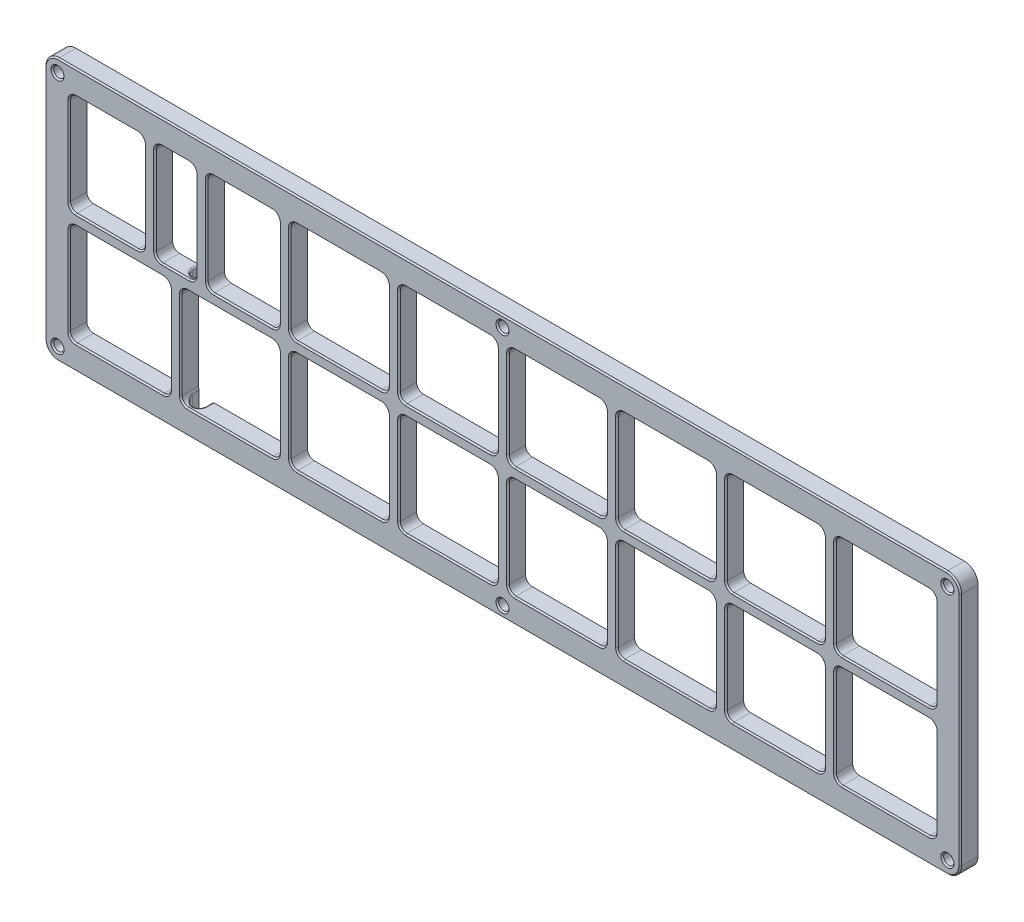
SolidWorks part; units mm, degrees
ref_plane "Front Plane" through (0, 0, 0) normal (0, 0, 1) x (1, 0, 0)
ref_plane "Top Plane" through (0, 0, 0) normal (0, 1, 0) x (1, 0, 0)
ref_plane "Right Plane" through (0, 0, 0) normal (1, 0, 0) x (0, 0, -1)
sketch "Sketch1" plane through (0, 0, 0) normal (0, 0, 1) x (1, 0, 0)
  line L1 (0, 40.25) -> (0, -40.25) construction
  line L2 (0, 0) -> (-160.25, 0) construction
  line L3 (-80.125, 0) -> (-80.125, 40.25) construction
  line L4 (168.25, -43.25) -> (168.25, 43.25)
  line L5 (163.25, 48.25) -> (-163.25, 48.25)
  line L6 (-168.25, 43.25) -> (-168.25, -43.25)
  line L7 (-163.25, -48.25) -> (163.25, -48.25)
  line L8 (168.25, -43.25) -> (168.25, 43.25)
  line L9 (163.25, 48.25) -> (-163.25, 48.25)
  line L10 (-168.25, 43.25) -> (-168.25, -43.25)
  line L11 (-163.25, -48.25) -> (163.25, -48.25)
  line L12 (-80.125, 20.125) -> (-160.25, 20.125) construction
  line L13 (-160.25, -40.25) -> (160.25, -40.25)
  line L14 (-160.25, 40.25) -> (-160.25, -40.25)
  line L15 (160.25, 40.25) -> (-160.25, 40.25)
  line L16 (160.25, -40.25) -> (160.25, 40.25)
  line L17 (-160.25, -40.25) -> (160.25, -40.25)
  line L18 (-160.25, 40.25) -> (-160.25, -40.25)
  line L19 (160.25, 40.25) -> (-160.25, 40.25)
  line L20 (160.25, -40.25) -> (160.25, 40.25)
  line L21 (-120.1875, 20.125) -> (-120.1875, 40.25) construction
  line L22 (-120.1875, 40.25) -> (-120.1875, -40.25) construction
  line L23 (-80.125, 40.25) -> (-80.125, -40.25) construction
  line L24 (-80.125, 20.125) -> (0, 20.125) construction
  line L25 (-40.0625, 20.125) -> (-40.0625, 40.25) construction
  line L26 (-40.0625, 40.25) -> (-40.0625, -40.25) construction
  line L27 (-42.0625, 40.25) -> (-42.0625, -40.25)
  line L28 (-82.125, 40.25) -> (-82.125, -40.25)
  line L29 (-122.1875, 40.25) -> (-122.1875, -40.25)
  line L30 (0, 2) -> (-160.25, 2)
  line L31 (-2, 40.25) -> (-2, -40.25)
  line L32 (-38.0625, 40.25) -> (-38.0625, -40.25)
  line L33 (-78.125, 40.25) -> (-78.125, -40.25)
  line L34 (-118.1875, 40.25) -> (-118.1875, -40.25)
  line L35 (0, -2) -> (-160.25, -2)
  line L36 (2, 40.25) -> (2, -40.25)
  line L37 (0, -2) -> (160.25, -2)
  line L38 (0, 2) -> (160.25, 2)
  line L39 (38.0625, 40.25) -> (38.0625, -40.25)
  line L40 (42.0625, 40.25) -> (42.0625, -40.25)
  line L41 (78.125, 40.25) -> (78.125, -40.25)
  line L42 (82.125, 40.25) -> (82.125, -40.25)
  line L43 (118.1875, 40.25) -> (118.1875, -40.25)
  line L44 (122.1875, 40.25) -> (122.1875, -40.25)
  line L45 (-159.25, 39.25) -> (-160.25, 39.25) construction
  line L46 (159.25, -39.25) -> (-159.25, -39.25)
  line L47 (159.25, -39.25) -> (159.25, 39.25)
  line L48 (159.25, 39.25) -> (-159.25, 39.25)
  line L49 (-159.25, -39.25) -> (-159.25, 39.25)
  line L50 (159.25, -39.25) -> (-159.25, 39.25) construction
  line L51 (159.25, 39.25) -> (-159.25, -39.25) construction
  line L52 (-159.25, 39.25) -> (-159.25, 40.25) construction
  circle A0 centre (163.5178, 43.5178) radius 1.75 construction
  circle A1 centre (0, 44.25) radius 1.75 construction
  circle A2 centre (-163.5178, 43.5178) radius 1.75 construction
  circle A3 centre (-163.5178, -43.5178) radius 1.75 construction
  arc A4 (163.25, -48.25) -> (168.25, -43.25) centre (163.25, -43.25) ccw
  arc A5 (168.25, 43.25) -> (163.25, 48.25) centre (163.25, 43.25) ccw
  arc A6 (-163.25, 48.25) -> (-168.25, 43.25) centre (-163.25, 43.25) ccw
  arc A7 (-168.25, -43.25) -> (-163.25, -48.25) centre (-163.25, -43.25) ccw
  arc A8 (163.25, -48.25) -> (168.25, -43.25) centre (163.25, -43.25) ccw
  arc A9 (168.25, 43.25) -> (163.25, 48.25) centre (163.25, 43.25) ccw
  arc A10 (-163.25, 48.25) -> (-168.25, 43.25) centre (-163.25, 43.25) ccw
  arc A11 (-168.25, -43.25) -> (-163.25, -48.25) centre (-163.25, -43.25) ccw
  circle A12 centre (0, -44.25) radius 1.75 construction
  circle A13 centre (163.5178, -43.5178) radius 1.75 construction
  circle A14 centre (163.5178, 43.5178) radius 1.75 construction
  circle A15 centre (0, 44.25) radius 1.75 construction
  circle A16 centre (-163.5178, 43.5178) radius 1.75 construction
  circle A17 centre (-163.5178, -43.5178) radius 1.75 construction
  circle A18 centre (0, -44.25) radius 1.75 construction
  circle A19 centre (163.5178, -43.5178) radius 1.75 construction
  circle A20 centre (-163.5178, 43.5178) radius 1.9
  circle A21 centre (0, 44.25) radius 1.9
  circle A22 centre (163.5178, 43.5178) radius 1.9
  circle A23 centre (163.5178, -43.5178) radius 1.9
  circle A24 centre (0, -44.25) radius 1.9
  circle A25 centre (-163.5178, -43.5178) radius 1.9
  dimension "D5" = 3.8
  dimension "D6" = 1
  dimension "D1" = 0
  dimension "D2" = 0
  dimension "D3" = 2
  dimension "D4" = 2
extrude "Boss-Extrude1" add sketch "Sketch1" along normal blind 6.5 contours L10 A11 L11 A8 L8 A9 L9 A10 A19 A18 A17 A16 A15 A14 L20 L17 L18 L19 | L35 L29 L30 L18 | L34 L19 L29 L30 | L35 L34 L30 L29 | L34 L35 L29 L17 | L35 L28 L30 L34 | L35 L33 L30 L28 | L33 L19 L28 L30 | L33 L35 L28 L17 | L35 L27 L30 L33 | L32 L19 L27 L30 | L32 L35 L27 L17 | L35 L32 L30 L27 | L35 L31 L30 L32 | L37 L35 L31 L17 L36 | L38 L30 L31 L35 L37 L36 | L30 L38 L36 L19 L31 | L39 L38 L36 L37 | L40 L19 L39 L38 | L40 L38 L39 L37 | L40 L37 L39 L17 | L41 L38 L40 L37 | L42 L19 L41 L38 | L42 L38 L41 L37 | L42 L37 L41 L17 | L43 L38 L42 L37 | L44 L19 L43 L38 | L44 L38 L43 L37 | L44 L37 L43 L17 | L38 L44 L37 L20 | L30 L49 L48 L29 L19 L18 | L48 L34 L19 L29 | L48 L28 L19 L34 | L48 L33 L19 L28 | L48 L27 L19 L33 | L48 L32 L19 L27 | L48 L31 L19 L32 | L48 L36 L19 L31 | L48 L39 L19 L36 | L48 L40 L19 L39 | L48 L41 L19 L40 | L48 L42 L19 L41 | L48 L43 L19 L42 | L48 L44 L19 L43 | L48 L47 L38 L20 L19 L44 | L47 L37 L20 L38 | L47 L46 L44 L17 L20 L37 | L44 L46 L43 L17 | L43 L46 L42 L17 | L42 L46 L41 L17 | L41 L46 L40 L17 | L40 L46 L39 L17 | L39 L46 L36 L17 | L36 L46 L31 L17 | L31 L46 L32 L17 | L32 L46 L27 L17 | L27 L46 L33 L17 | L33 L46 L28 L17 | L28 L46 L34 L17 | L34 L46 L29 L17 | L46 L49 L35 L18 L17 L29 | L35 L49 L30 L18
sketch "Sketch2" plane through (0, 0, 6.5) normal (0, 0, 1) x (1, 0, 0)
  line L0 (-122.1875, 39.25) -> (-122.1875, 2) construction
  line L1 (-122.1875, 39.25) -> (-118.1875, 39.25)
  line L2 (-122.1875, 39.25) -> (-122.1875, 2)
  line L3 (-122.1875, 2) -> (-118.1875, 2)
  line L4 (-118.1875, 39.25) -> (-118.1875, 2)
  line L5 (-122.1875, 39.25) -> (-159.25, 39.25) construction
  point P6 (-122.1875, 39.25)
  point P9 (-122.1875, 39.25)
extrude "Cut-Extrude1" cut sketch "Sketch2" against normal up to next
sketch "Sketch3" plane through (0, 0, 0) normal (0, 0, -1) x (-1, 0, 0)
  line L0 (120.1875, 39.25) -> (120.1875, 2) construction
  line L2 (82.125, 2) -> (159.25, 2) construction
  line L3 (78.125, 2) -> (82.125, 2) construction
  line L4 (118.1875, -2) -> (122.1875, -2) construction
  line L5 (108.6875, 39.25) -> (112.6875, 39.25)
  line L6 (108.6875, 39.25) -> (108.6875, 2)
  line L7 (108.6875, 2) -> (112.6875, 2)
  line L8 (112.6875, 39.25) -> (112.6875, 2)
  line L9 (131.6875, 39.25) -> (127.6875, 39.25)
  line L10 (131.6875, 39.25) -> (131.6875, 2)
  line L11 (131.6875, 2) -> (127.6875, 2)
  line L12 (127.6875, 39.25) -> (127.6875, 2)
  line L13 (82.125, 39.25) -> (159.25, 39.25) construction
  point P2 (108.6875, 39.25)
  point P6 (120.1875, -2)
  point P24 (120.1875, 39.25)
  dimension "D1" = 15
extrude "Boss-Extrude2" add sketch "Sketch3" against normal up to surface (6.5 mm away) up to face at (-120.6875, 20.625, 6.5)
sketch "Sketch4" plane through (0, -48.25, 0) normal (0, -1, 0) x (1, 0, 0)
  line L0 (-82.125, 6.5) -> (-118.1875, 6.5) construction
  line L1 (-82.125, 6.5) -> (-118.1875, 6.5) construction
  line L2 (-112.6875, 6.5) -> (-127.6875, 6.5) construction
  line L3 (-112.6875, 6.5) -> (-127.6875, 6.5) construction
  line L4 (-118.1875, 6.5) -> (-112.6875, 6.5) construction
  line L5 (-115.4375, 6.5) -> (-115.4375, 0) construction
  line L6 (-163.25, 0) -> (163.25, 0) construction
  line L7 (-117.9375, 2.5) -> (-117.9375, 0)
  line L8 (-112.9375, 2.5) -> (-112.9375, 0)
  line L9 (-117.9375, 0) -> (-112.9375, 0)
  arc A0 (-112.9375, 2.5) -> (-117.9375, 2.5) centre (-115.4375, 2.5) ccw
  point P4 (-115.4375, 6.5)
  dimension "D1" = 5
extrude "Cut-Extrude2" cut sketch "Sketch4" against normal up to surface (50.25 mm away) up to face at (-95.4062, 2, 3.25)
fillet "Fillet1" radius 2.5 68 edges at (-159.25, -2, 3.25) (-159.25, -39.25, 3.25) (-122.1875, -39.25, 3.25) (-38.0625, 39.25, 3.25) (-38.0625, 2, 3.25) (-2, 2, 3.25) (-118.1875, -2, 3.25) (-118.1875, -39.25, 3.25) (-82.125, -39.25, 3.25) (-78.125, 39.25, 3.25) (-78.125, 2, 3.25) (-42.0625, 2, 3.25) (-78.125, -2, 3.25) (-78.125, -39.25, 3.25) (-42.0625, -39.25, 3.25) (38.0625, 2, 3.25) (2, 39.25, 3.25) (2, 2, 3.25) (78.125, 2, 3.25) (42.0625, 2, 3.25) (118.1875, 2, 3.25) (82.125, 2, 3.25) (159.25, 2, 3.25) (122.1875, 2, 3.25) (122.1875, -39.25, 3.25) (159.25, -39.25, 3.25) (122.1875, -2, 3.25) (82.125, -39.25, 3.25) (118.1875, -39.25, 3.25) (82.125, -2, 3.25) (42.0625, -39.25, 3.25) (78.125, -39.25, 3.25) (42.0625, -2, 3.25) (2, -39.25, 3.25) (38.0625, -39.25, 3.25) (2, -2, 3.25) (-38.0625, -2, 3.25) (-38.0625, -39.25, 3.25) (-2, -39.25, 3.25) (-159.25, 39.25, 3.25) (-159.25, 2, 3.25) (-131.6875, 2, 3.25) (-127.6875, 2, 3.25) (-112.6875, 2, 3.25) (-127.6875, 39.25, 3.25) (-108.6875, 2, 3.25) (-82.125, 2, 3.25) (-108.6875, 39.25, 3.25) (42.0625, 39.25, 3.25) (82.125, 39.25, 3.25) (122.1875, 39.25, 3.25) (-122.1875, -2, 3.25) (-82.125, -2, 3.25) (-42.0625, -2, 3.25) (-2, -2, 3.25) (38.0625, -2, 3.25) (78.125, -2, 3.25) (118.1875, -2, 3.25) (159.25, -2, 3.25) (-131.6875, 39.25, 3.25) (-112.6875, 39.25, 3.25) (-82.125, 39.25, 3.25) (-42.0625, 39.25, 3.25) (-2, 39.25, 3.25) (38.0625, 39.25, 3.25) (78.125, 39.25, 3.25) (118.1875, 39.25, 3.25) (159.25, 39.25, 3.25)
fillet "Fillet2" radius 0.5 15 edges at (-117.9375, 2, 1.25) (-112.9375, 3.4103, 1.25) (-113.3623, 2.7916, 3.8941) (-112.9375, -2, 1.25) (-117.9375, -3.4103, 1.25) (-117.5127, -2.7916, 3.8941) (-112.9375, -39.25, 1.25) (-117.9375, -37.8397, 1.25) (-117.1466, -38.78, 4.3245) (-117.9375, -48.25, 1.25) (-115.4375, -48.25, 5) (-117.1146, 2, 4.354) (-113.7604, -2, 4.354) (-113.7604, -39.25, 4.354) (-112.9375, -48.25, 1.25)
chamfer "Chamfer1" distance 0.5 angle 45 156 edges at (-166.7855, 46.7855, 6.5) (0, 48.25, 6.5) (166.7855, 46.7855, 6.5) (168.25, 0, 6.5) (166.7855, -46.7855, 6.5) (0, -48.25, 6.5) (-166.7855, -46.7855, 6.5) (-168.25, 0, 6.5) (-161.6178, 43.5178, 6.5) (-161.6178, 43.5178, 0) (1.9, 44.25, 6.5) (1.9, 44.25, 0) (165.4178, 43.5178, 6.5) (165.4178, 43.5178, 0) (165.4178, -43.5178, 6.5) (165.4178, -43.5178, 0) (1.9, -44.25, 6.5) (1.9, -44.25, 0) (-161.6178, -43.5178, 6.5) (-161.6178, -43.5178, 0) (-158.5178, -2.7322, 6.5) (-159.25, -20.625, 6.5) (-158.5178, -38.5178, 6.5) (-140.7188, -39.25, 6.5) (-122.9197, -38.5178, 6.5) (-122.1875, -20.625, 6.5) (-122.9197, -2.7322, 6.5) (-140.7188, -2, 6.5) (-37.3303, 38.5178, 6.5) (-38.0625, 20.625, 6.5) (-37.3303, 2.7322, 6.5) (-20.0312, 2, 6.5) (-2.7322, 2.7322, 6.5) (-2, 20.625, 6.5) (-2.7322, 38.5178, 6.5) (-20.0312, 39.25, 6.5) (-117.4553, -2.7322, 6.5) (-118.1875, -20.625, 6.5) (-117.4553, -38.5178, 6.5) (-100.1562, -39.25, 6.5) (-82.8572, -38.5178, 6.5) (-82.125, -20.625, 6.5) (-82.8572, -2.7322, 6.5) (-100.1562, -2, 6.5) (-77.3928, 38.5178, 6.5) (-78.125, 20.625, 6.5) (-77.3928, 2.7322, 6.5) (-60.0938, 2, 6.5) (-42.7947, 2.7322, 6.5) (-42.0625, 20.625, 6.5) (-42.7947, 38.5178, 6.5) (-60.0937, 39.25, 6.5) (-77.3928, -2.7322, 6.5) (-78.125, -20.625, 6.5) (-77.3928, -38.5178, 6.5) (-60.0938, -39.25, 6.5) (-42.7947, -38.5178, 6.5) (-42.0625, -20.625, 6.5) (-42.7947, -2.7322, 6.5) (-60.0937, -2, 6.5) (37.3303, 2.7322, 6.5) (38.0625, 20.625, 6.5) (37.3303, 38.5178, 6.5) (20.0312, 39.25, 6.5) (2.7322, 38.5178, 6.5) (2, 20.625, 6.5) (2.7322, 2.7322, 6.5) (20.0312, 2, 6.5) (77.3928, 2.7322, 6.5) (78.125, 20.625, 6.5) (77.3928, 38.5178, 6.5) (60.0937, 39.25, 6.5) (42.7947, 38.5178, 6.5) (42.0625, 20.625, 6.5) (42.7947, 2.7322, 6.5) (60.0937, 2, 6.5) (117.4553, 2.7322, 6.5) (118.1875, 20.625, 6.5) (117.4553, 38.5178, 6.5) (100.1562, 39.25, 6.5) (82.8572, 38.5178, 6.5) (82.125, 20.625, 6.5) (82.8572, 2.7322, 6.5) (100.1562, 2, 6.5) (158.5178, 2.7322, 6.5) (159.25, 20.625, 6.5) (158.5178, 38.5178, 6.5) (140.7187, 39.25, 6.5) (122.9197, 38.5178, 6.5) (122.1875, 20.625, 6.5) (122.9197, 2.7322, 6.5) (140.7187, 2, 6.5) (122.9197, -38.5178, 6.5) (140.7187, -39.25, 6.5) (158.5178, -38.5178, 6.5) (159.25, -20.625, 6.5) (158.5178, -2.7322, 6.5) (140.7187, -2, 6.5) (122.9197, -2.7322, 6.5) (122.1875, -20.625, 6.5) (82.8572, -38.5178, 6.5) (100.1562, -39.25, 6.5) (117.4553, -38.5178, 6.5) (118.1875, -20.625, 6.5) (117.4553, -2.7322, 6.5) (100.1562, -2, 6.5) (82.8572, -2.7322, 6.5) (82.125, -20.625, 6.5) (42.7947, -38.5178, 6.5) (60.0937, -39.25, 6.5) (77.3928, -38.5178, 6.5) (78.125, -20.625, 6.5) (77.3928, -2.7322, 6.5) (60.0937, -2, 6.5) (42.7947, -2.7322, 6.5) (42.0625, -20.625, 6.5) (2.7322, -38.5178, 6.5) (20.0312, -39.25, 6.5) (37.3303, -38.5178, 6.5) (38.0625, -20.625, 6.5) (37.3303, -2.7322, 6.5) (20.0312, -2, 6.5) (2.7322, -2.7322, 6.5) (2, -20.625, 6.5) (-37.3303, -2.7322, 6.5) (-38.0625, -20.625, 6.5) (-37.3303, -38.5178, 6.5) (-20.0312, -39.25, 6.5) (-2.7322, -38.5178, 6.5) (-2, -20.625, 6.5) (-2.7322, -2.7322, 6.5) (-20.0312, -2, 6.5) (-158.5178, 38.5178, 6.5) (-159.25, 20.625, 6.5) (-158.5178, 2.7322, 6.5) (-145.4687, 2, 6.5) (-132.4197, 2.7322, 6.5) (-131.6875, 20.625, 6.5) (-132.4197, 38.5178, 6.5) (-145.4687, 39.25, 6.5) (-126.9553, 2.7322, 6.5) (-120.1875, 2, 6.5) (-113.4197, 2.7322, 6.5) (-112.6875, 20.625, 6.5) (-113.4197, 38.5178, 6.5) (-120.1875, 39.25, 6.5) (-126.9553, 38.5178, 6.5) (-127.6875, 20.625, 6.5) (-107.9553, 2.7322, 6.5) (-95.4062, 2, 6.5) (-82.8572, 2.7322, 6.5) (-82.125, 20.625, 6.5) (-82.8572, 38.5178, 6.5) (-95.4062, 39.25, 6.5) (-107.9553, 38.5178, 6.5) (-108.6875, 20.625, 6.5)
